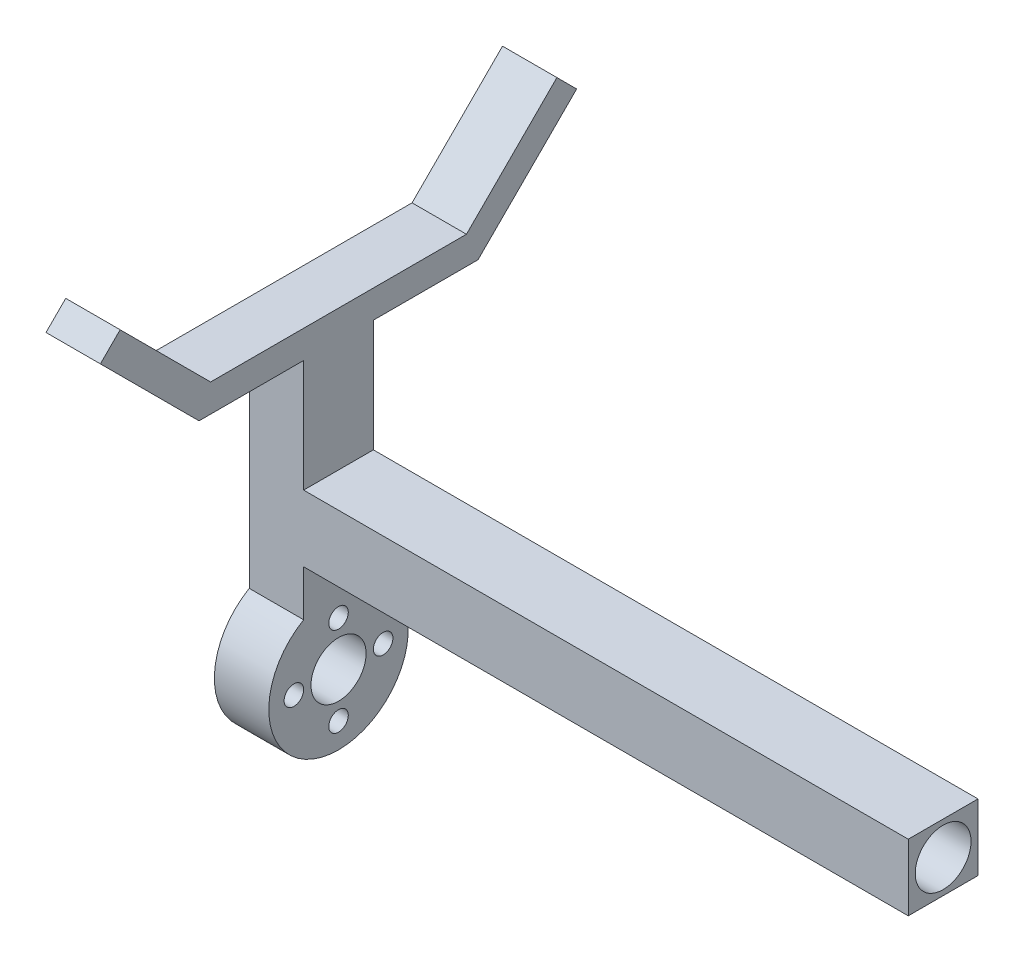
SolidWorks part; units mm, degrees
ref_plane "Front Plane" through (0, 0, 0) normal (0, 0, 1) x (1, 0, 0)
ref_plane "Top Plane" through (0, 0, 0) normal (0, 1, 0) x (1, 0, 0)
ref_plane "Right Plane" through (0, 0, 0) normal (1, 0, 0) x (0, 0, -1)
sketch "Sketch1" plane through (0, 0, 0) normal (1, 0, 0) x (0, 0, -1)
  line L0 (0, 0) -> (-27.0167, 0) construction
  line L2 (-6.35, 10.9985) -> (-6.35, 51.8925)
  line L3 (-6.35, 51.8925) -> (6.35, 51.8925)
  line L4 (6.35, 10.9985) -> (6.35, 51.8925)
  line L5 (0, 0) -> (12.7, 0) construction
  line L6 (-27.0167, 0) -> (-27.0167, 51.8925) construction
  line L7 (-6.35, 51.8925) -> (-27.0167, 51.8925) construction
  circle A0 centre (0, 0) radius 5.0165
  arc A1 (-6.35, 10.9985) -> (6.35, 10.9985) centre (0, 0) ccw
  circle A2 centre (-8.128, 0) radius 1.778
  circle A9 centre (0, 8.128) radius 1.778
  circle A10 centre (8.128, 0) radius 1.778
  circle A11 centre (0, -8.128) radius 1.778
  point P0 (0, 0)
  point P16 (0, 0)
  point P19 (0, 0)
  point P22 (0, -45.974)
  point P23 (0, 11.6075)
  point P24 (0, 0)
  point P27 (0, 0)
  dimension "D3" = 10.033
  dimension "D4" = 25.4
  dimension "D5" = 40.894
  dimension "D1" = 3.556
  dimension "D2" = 12.7
  dimension "D6" = 8.128
  dimension "D7" = 4
extrude "Boss-Extrude1" add sketch "Sketch1" along normal blind 9.906
sketch "Sketch3" plane through (0, 0, 0) normal (1, 0, 0) x (0, 0, -1)
  line L0 (0, 51.8925) -> (0, 78.5764) construction
  line L1 (6.35, 51.8925) -> (-6.35, 51.8925) construction
  line L2 (0, 55) -> (0, -55) construction
  line L3 (25.4, 51.8925) -> (-25.4, 51.8925)
  line L4 (-25.4, 51.8925) -> (-43.3605, 69.853)
  line L5 (0, 51.8925) -> (0, 56.9725)
  line L6 (23.2958, 56.9725) -> (-23.2958, 56.9725)
  line L7 (-43.3605, 69.853) -> (-39.7684, 73.4451)
  line L8 (-39.7684, 73.4451) -> (-23.2958, 56.9725)
  line L9 (25.4, 51.8925) -> (43.3605, 69.853)
  line L10 (39.7684, 73.4451) -> (23.2958, 56.9725)
  line L11 (43.3605, 69.853) -> (39.7684, 73.4451)
  dimension "D1" = 25.4
  dimension "D2" = 5.08
  dimension "D3" = 25.4
  dimension "D4" = 45
  dimension "D5" = 135
  dimension "D7" = 5.08
extrude "Boss-Extrude2" add sketch "Sketch3" along normal blind 9.906 contours L8 L7 L4 L3 L5 L6 | L9 L11 L10 L6 L5 L3
sketch "Sketch4" plane through (0, 0, 0) normal (-1, 0, 0) x (0, 0, 1)
  line L0 (0, 12.7) -> (0, 38.1) construction
  line L1 (0, -5.4483) -> (0, 5.4483) construction
  line L2 (6.35, 51.8925) -> (6.35, 10.9985) construction
  line L3 (-6.35, 19.3545) -> (6.35, 19.3545)
  line L4 (-6.35, 19.3545) -> (-6.35, 31.4455)
  line L5 (-6.35, 31.4455) -> (6.35, 31.4455)
  line L6 (6.35, 19.3545) -> (6.35, 31.4455)
  line L7 (-6.35, 19.3545) -> (6.35, 31.4455) construction
  line L8 (-6.35, 31.4455) -> (6.35, 19.3545) construction
  circle A0 centre (0, 0) radius 12.7 construction
  point P9 (0, 25.4)
  dimension "D1" = 25.4
extrude "Boss-Extrude3" add sketch "Sketch4" against normal blind 110.094 from offset 9.906 offset against normal yes
sketch "Sketch5" plane through (120, 0, 0) normal (1, 0, 0) x (0, 0, -1)
  circle A0 centre (0, 25.4) radius 5.08
extrude "Cut-Extrude1" cut sketch "Sketch5" against normal blind 12.7
